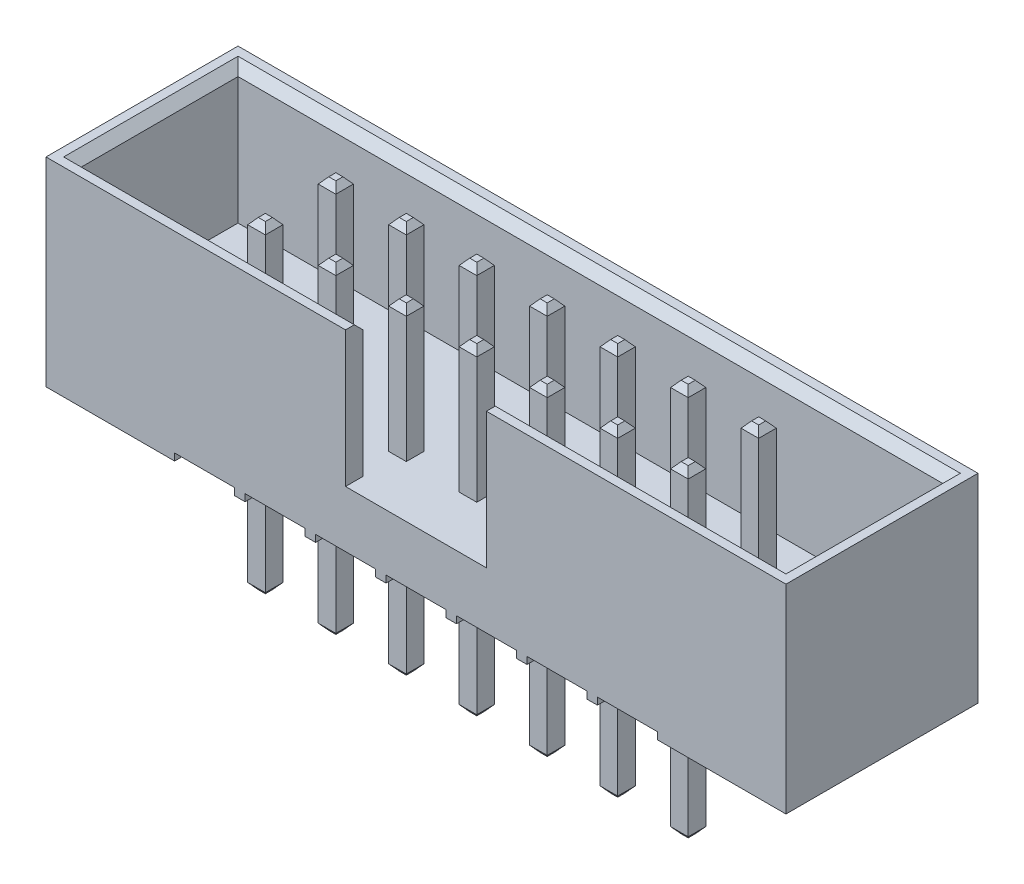
SolidWorks part; units mm, degrees
ref_plane "Спереди" through (0, 0, 0) normal (0, 0, 1) x (1, 0, 0)
ref_plane "Сверху" through (0, 0, 0) normal (0, 1, 0) x (1, 0, 0)
ref_plane "Справа" through (0, 0, 0) normal (1, 0, 0) x (0, 0, -1)
ref_plane "Плоскость1" through (0, -3.6, 0) normal (0, 1, 0) x (1, 0, 0)
sketch "Эскиз1" plane through (0, 0, 0) normal (0, 1, 0) x (1, 0, 0)
  line L1 (0, 0) -> (21, 0)
  line L2 (0, 0) -> (0, 5.45)
  line L3 (0, 5.45) -> (21, 5.45)
  line L4 (21, 0) -> (21, 5.45)
  dimension "D1" = 5.45
  dimension "A" = 21
extrude "Корпус" add sketch "Эскиз1" along normal blind 5.65
sketch "Эскиз6" plane through (0, 0, 0) normal (0, 0, 1) x (1, 0, 0)
  line L0 (0, 5.65) -> (0, 0) construction
  line L1 (3.65, 0) -> (5.35, 0)
  line L2 (3.65, 0) -> (3.65, 0.2)
  line L3 (3.65, 0.2) -> (5.35, 0.2)
  line L4 (5.35, 0) -> (5.35, 0.2)
  line L5 (3.65, 0) -> (5.35, 0.2) construction
  line L6 (3.65, 0.2) -> (5.35, 0) construction
  line L7 (0, 0) -> (21, 0) construction
  point P0 (4.5, 0.1)
  dimension "D1" = 1.7
  dimension "D2" = 4.5
  dimension "D3" = 0.2
extrude "Вырез-Вытянуть7" cut sketch "Эскиз6" against normal through all
pattern_linear "Линейный массив3" count 7 spacing 2 along (1, 0, 0) of "Вырез-Вытянуть7"
sketch "Эскиз2" plane through (0, 5.65, 0) normal (0, 1, 0) x (1, 0, 0)
  line L0 (0, 5.45) -> (0, 0) construction
  line L1 (0.5, 0.5) -> (20.5, 0.5)
  line L2 (0.5, 0.5) -> (0.5, 4.95)
  line L3 (0.5, 4.95) -> (20.5, 4.95)
  line L4 (21, 5.45) -> (0, 5.45) construction
  line L7 (0, 0) -> (21, 0) construction
  line L8 (21, 0) -> (21, 5.45) construction
  line L12 (20.5, 0.5) -> (20.5, 4.95)
  dimension "D2" = 0.5
  dimension "D3" = 0.5
  dimension "D4" = 0.5
  dimension "D1" = 0.5
extrude "Вырез-Вытянуть2" cut sketch "Эскиз2" against normal offset from surface (3.85 mm away) 1.8 up to face at (19.175, 0, -2.725)
sketch "Эскиз3" plane through (0, 0, 0) normal (0, 0, 1) x (1, 0, 0)
  line L0 (0, 5.65) -> (21, 5.65) construction
  line L1 (8.5, 1.8) -> (12.5, 1.8)
  line L2 (8.5, 1.8) -> (8.5, 5.65)
  line L3 (8.5, 5.65) -> (12.5, 5.65)
  line L4 (12.5, 1.8) -> (12.5, 5.65)
  line L5 (8.5, 1.8) -> (12.5, 5.65) construction
  line L6 (8.5, 5.65) -> (12.5, 1.8) construction
  line L9 (10.5, 5.65) -> (10.5, 1.8) construction
  line L10 (0, 5.65) -> (0, 0) construction
  line L11 (21, 5.65) -> (21, 0) construction
  line L12 (0.5, 1.8) -> (20.5, 1.8) construction
  point P0 (10.5, 3.725)
  dimension "D1" = 4
extrude "Вырез-Вытянуть3" cut sketch "Эскиз3" against normal up to next
sketch "Эскиз5" plane through (0, -3.6, 0) normal (0, 1, 0) x (1, 0, 0)
  line L0 (4.25, 1.975) -> (4.5, 1.725) construction
  line L1 (4.25, 3.975) -> (4.5, 3.725) construction
  line L2 (4.5, 3.725) -> (4.75, 3.475) construction
  line L3 (4.5, 1.725) -> (4.75, 1.475) construction
  line L6 (0, 0) -> (8.5, 0) construction
  line L9 (4.25, 1.975) -> (4.75, 1.975)
  line L10 (4.25, 1.975) -> (4.25, 1.475)
  line L11 (4.25, 1.475) -> (4.75, 1.475)
  line L12 (4.75, 1.975) -> (4.75, 1.475)
  line L14 (4.25, 1.475) -> (4.75, 1.975) construction
  line L15 (4.25, 3.975) -> (4.75, 3.975)
  line L16 (4.25, 3.975) -> (4.25, 3.475)
  line L17 (4.25, 3.475) -> (4.75, 3.475)
  line L18 (4.75, 3.975) -> (4.75, 3.475)
  line L20 (4.25, 3.475) -> (4.75, 3.975) construction
  line L24 (0, 5.45) -> (0, 0) construction
  point P0 (4.5, 1.725)
  dimension "D1" = 0.5
  dimension "D2" = 2
  dimension "D3" = 4.5
  dimension "D4" = 1.725
extrude "Контакты" add sketch "Эскиз5" along normal offset from surface (9.15 mm away) 0.1 up to face at (10.5, 5.65, -1.9)
chamfer "Фаска (корпус)" distance 0.25 angle 45 5 edges at (16.5, 5.65, -0.5) (20.5, 5.65, -2.725) (4.5, 5.65, -0.5) (0.5, 5.65, -2.725) (10.5, 5.65, -4.95)
chamfer "Фаска (контакты)" distance 0.15 angle 50 16 edges at (4.5, -3.6, -3.975) (4.25, -3.6, -3.725) (4.5, -3.6, -3.475) (4.75, -3.6, -3.725) (4.5, -3.6, -1.975) (4.25, -3.6, -1.725) (4.5, -3.6, -1.475) (4.75, -3.6, -1.725) (4.75, 5.55, -3.725) (4.5, 5.55, -3.475) (4.25, 5.55, -3.725) (4.5, 5.55, -3.975) (4.75, 5.55, -1.725) (4.5, 5.55, -1.475) (4.25, 5.55, -1.725) (4.5, 5.55, -1.975)
pattern_linear "Линейный массив2" count 7 spacing 2 along (1, 0, 0) of "Контакты", "Фаска (контакты)"
